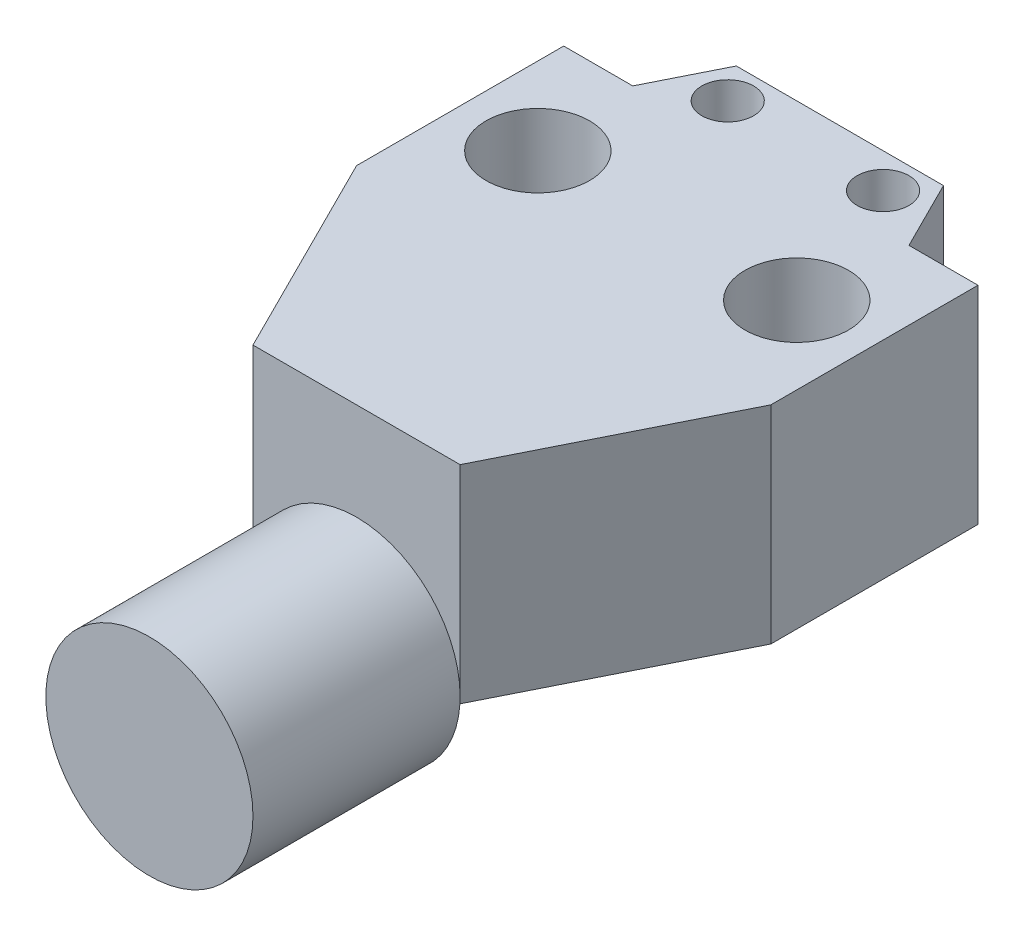
SolidWorks part; units mm, degrees
ref_plane "Front Plane" through (0, 0, 0) normal (0, 0, 1) x (1, 0, 0)
ref_plane "Top Plane" through (0, 0, 0) normal (0, 1, 0) x (1, 0, 0)
ref_plane "Right Plane" through (0, 0, 0) normal (1, 0, 0) x (0, 0, -1)
sketch "Sketch1" plane through (0, 0, 0) normal (0, 1, 0) x (1, 0, 0)
  line L0 (158.75, -79.375) -> (79.375, -238.125)
  line L2 (-158.75, -79.375) -> (-158.75, 79.375)
  line L4 (158.75, -79.375) -> (158.75, 79.375)
  line L5 (-158.75, -79.375) -> (158.75, 79.375) construction
  line L6 (-158.75, 79.375) -> (158.75, -79.375) construction
  line L7 (-158.75, -79.375) -> (-79.375, -238.125)
  line L8 (-79.375, -238.125) -> (79.375, -238.125)
  line L9 (0, -7.8142) -> (0, 7.8142) construction
  line L10 (-7.8142, 0) -> (7.8142, 0) construction
  line L11 (-105.8333, 79.375) -> (-79.375, 132.2917)
  line L13 (79.375, 132.2917) -> (105.8333, 79.375)
  line L14 (-158.75, 79.375) -> (-105.8333, 79.375)
  line L15 (105.8333, 79.375) -> (158.75, 79.375)
  line L16 (79.375, 132.2917) -> (0, 132.2917)
  line L17 (0, 132.2917) -> (-79.375, 132.2917)
  circle A0 centre (-99.2188, 0) radius 39.6875
  circle A1 centre (99.2188, 0) radius 39.6875
  circle A2 centre (-59.5312, 105.8333) radius 19.8438
  circle A3 centre (59.5312, 105.8333) radius 19.8438
  point P0 (0, 0)
  point P24 (7.7424, 6.35)
  point P25 (-6.1407, 6.35)
  point P26 (-6.9716, 6.35)
  point P27 (7.6084, 6.35)
  point P28 (-7.5076, 6.35)
  point P29 (0, 0)
  dimension "Grasper Diameter" = 79.375
  dimension "Knuckle Hole Diameter" = 39.6875
  dimension "Joint Length" = 317.5
  dimension "Joint Width" = 158.75
  dimension "Joint Width2" = 158.75
  dimension "Wrist Diameter" = 158.75
  dimension "Wrist Diameter Div2" = 79.375
  dimension "Grasper Diameter Spacing1" = 99.2188
  dimension "Graspher Diameter Spacing" = 99.2188
  dimension "Knuckle Length" = 52.9167
  dimension "Knuckle Spacing" = 59.5312
  dimension "Knuckle Spacing1" = 59.5312
  dimension "Knuckle Height" = 26.4583
  dimension "End Knuckle Width" = 79.375
  dimension "Lower Knuckle Width" = 105.8333
extrude "Boss-Extrude1" add sketch "Sketch1" along normal blind 158.75
sketch "Sketch2" plane through (0, 0, 238.125) normal (0, 0, 1) x (1, 0, 0)
  line L0 (0, -7.8142) -> (0, 7.8142) construction
  circle A0 centre (0, 4.8423) radius 79.375
  dimension "Linkage Diameter" = 158.75
extrude "Boss-Extrude2" add sketch "Sketch2" along normal blind 158.75
